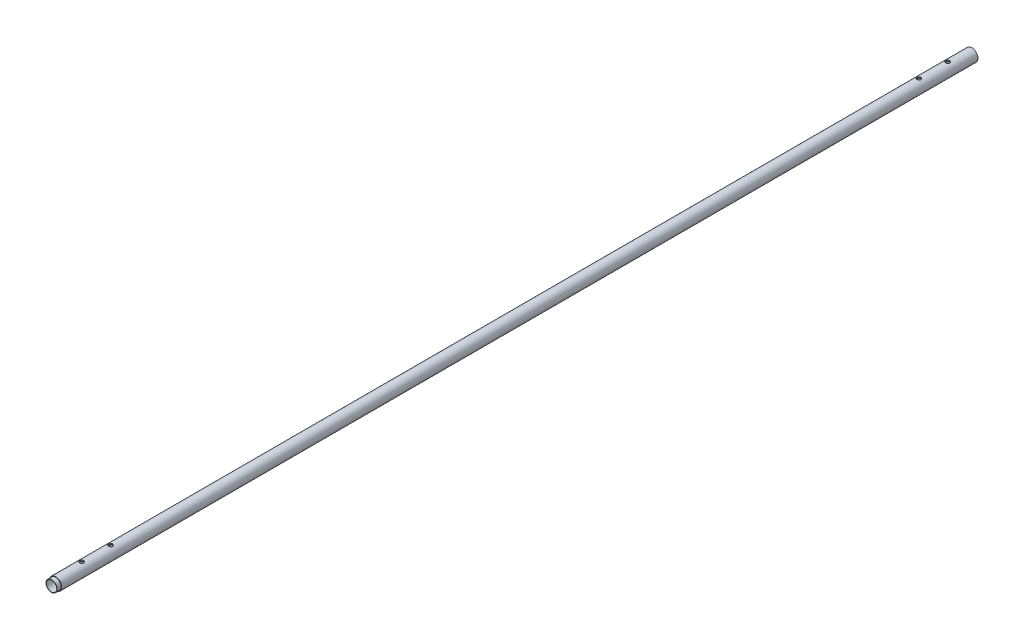
SolidWorks part; units mm, degrees
ref_plane "Front Plane" through (0, 0, 0) normal (0, 0, 1) x (1, 0, 0)
ref_plane "Top Plane" through (0, 0, 0) normal (0, 1, 0) x (1, 0, 0)
ref_plane "Right Plane" through (0, 0, 0) normal (1, 0, 0) x (0, 0, -1)
sketch "Sketch1" plane through (0, 0, 0) normal (0, 0, 1) x (1, 0, 0)
  circle A0 centre (0, 0) radius 10.65
  circle A1 centre (0, 0) radius 9
  dimension "D1" = 21.3
  dimension "D2" = 18
extrude "Boss-Extrude1" add sketch "Sketch1" along normal blind 1594
sketch "Sketch2" plane through (0, 0, 0) normal (0, 1, 0) x (1, 0, 0)
  line L0 (-10.65, -1594) -> (10.65, -1594) construction
  line L1 (10.65, 0) -> (-10.65, 0) construction
  circle A0 centre (0, -1542) radius 3.5
  circle A1 centre (0, -1492) radius 3.5
  circle A2 centre (0, -42) radius 3.5
  circle A3 centre (0, -92) radius 3.5
  dimension "D1" = 52
  dimension "D2" = 7
  dimension "D3" = 7
  dimension "D4" = 50
  dimension "D5" = 7
  dimension "D6" = 42
  dimension "D7" = 7
  dimension "D8" = 50
extrude "Cut-Extrude1" cut sketch "Sketch2" against normal through all both and the other way through all
sketch "Sketch3" plane through (0, 0, 0) normal (1, 0, 0) x (0, 0, -1)
  line L0 (-1594, 0) -> (-1556.692, 0)
  line L1 (-1594, 10.65) -> (-1587, 10.65)
  line L2 (-1594, 10.65) -> (-1594, 9.65)
  line L3 (-1594, 9.65) -> (-1587, 9.65)
  line L4 (-1587, 10.65) -> (-1587, 9.65)
  line L5 (-1594, 10.65) -> (-1594, -10.65) construction
  dimension "D1" = 7
  dimension "D2" = 1
revolve "Cut-Revolve1" cut sketch "Sketch3" angle 360 about L0
